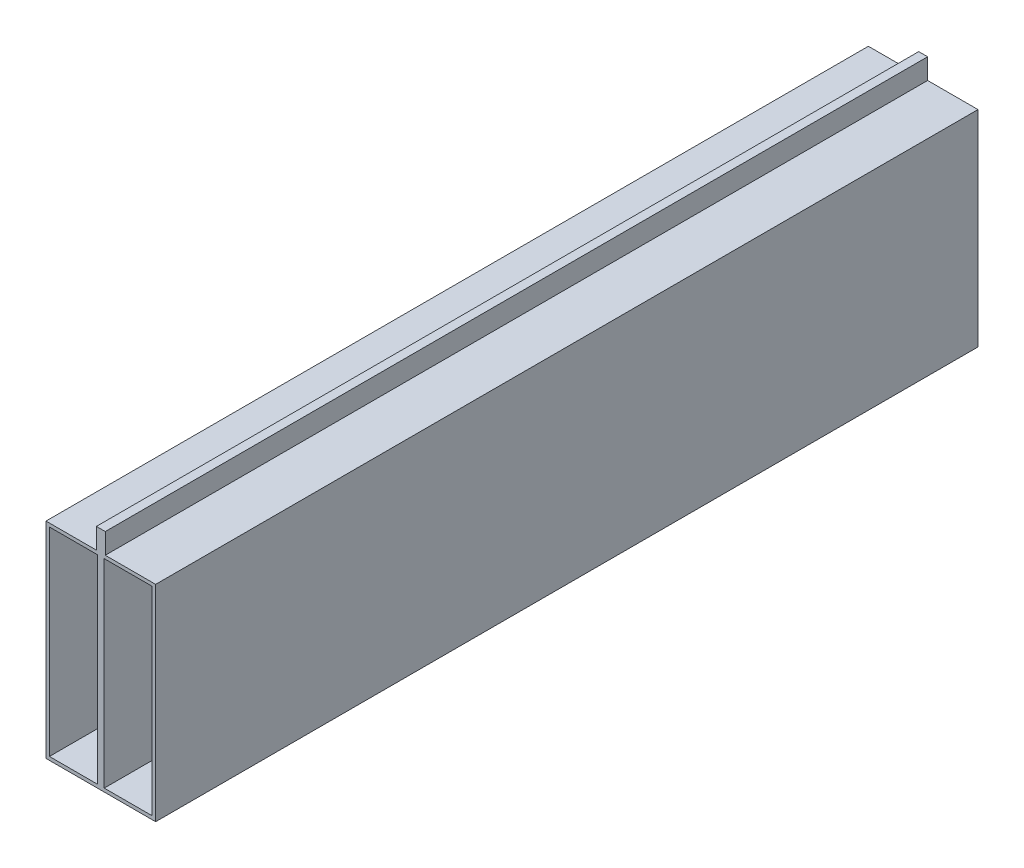
SolidWorks part; units mm, degrees
ref_plane "Plan de face" through (0, 0, 0) normal (0, 0, 1) x (1, 0, 0)
ref_plane "Plan de dessus" through (0, 0, 0) normal (0, 1, 0) x (1, 0, 0)
ref_plane "Plan de droite" through (0, 0, 0) normal (1, 0, 0) x (0, 0, -1)
sketch "Esquisse1" plane through (0, 0, 0) normal (0, 0, 1) x (1, 0, 0)
  line L0 (425, 1475) -> (425, 25)
  line L1 (0, 0) -> (800, 0)
  line L2 (0, 0) -> (0, 1500)
  line L3 (0, 1500) -> (800, 1500)
  line L4 (800, 0) -> (800, 1500)
  line L5 (25, 1475) -> (375, 1475)
  line L6 (25, 1475) -> (25, 25)
  line L7 (25, 25) -> (375, 25)
  line L8 (375, 1475) -> (375, 25)
  line L9 (425, 25) -> (775, 25)
  line L10 (775, 25) -> (775, 1475)
  line L11 (775, 1475) -> (425, 1475)
  line L12 (400, -1) -> (400, 1) construction
  point P16 (400, 0)
  dimension "D1" = 1500
  dimension "D2" = 800
  dimension "D3" = 25
  dimension "D4" = 25
  dimension "D5" = 25
  dimension "D6" = 25
  dimension "D7" = 25
  dimension "D8" = 25
  dimension "D9" = 25
  dimension "D10" = 25
extrude "Boss.-Extru.1" add sketch "Esquisse1" against normal blind 6000
sketch "Esquisse2" plane through (0, 0, 0) normal (0, 0, 1) x (1, 0, 0)
  line L0 (400, 1500) -> (400, 1546.5728) construction
  line L1 (800, 1500) -> (0, 1500) construction
  line L2 (367.5, 1500) -> (432.5, 1500)
  line L3 (432.5, 1500) -> (432.5, 1650)
  line L4 (432.5, 1650) -> (367.5, 1650)
  line L5 (367.5, 1650) -> (367.5, 1500)
  point P7 (400, 1500)
  dimension "D1" = 65
  dimension "D2" = 150
extrude "Boss.-Extru.2" add sketch "Esquisse2" against normal up to surface (6000 mm away) up to face at (600, 750, -6000)
